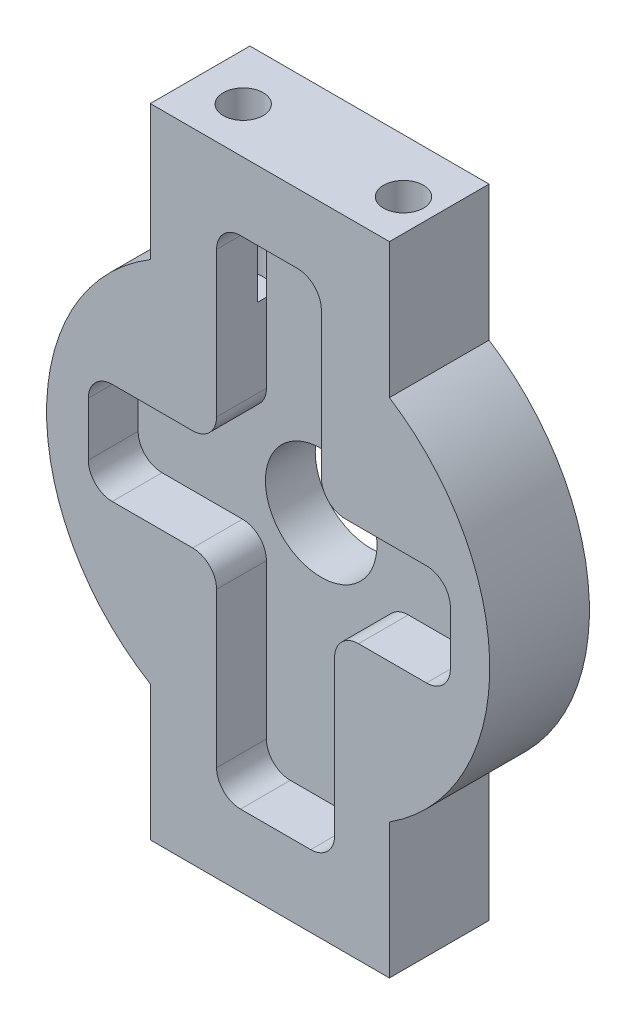
SolidWorks part; units mm, degrees
ref_plane "Front Plane" through (0, 0, 0) normal (0, 0, 1) x (1, 0, 0)
ref_plane "Top Plane" through (0, 0, 0) normal (0, 1, 0) x (1, 0, 0)
ref_plane "Right Plane" through (0, 0, 0) normal (1, 0, 0) x (0, 0, -1)
other "Graphic1"
ref_plane "Plane1" through (0, 0, 10) normal (0, 0, 1) x (1, 0, 0)
sketch "Sketch1" plane through (0, 0, 10) normal (0, 0, 1) x (1, 0, 0)
  line L0 (-246.9356, 240) -> (-246.9356, 200) construction
  line L1 (-257.9579, 223.6814) -> (-221.137, 223.6814) construction
  line L2 (-253, 240) -> (-241, 240)
  line L3 (-241, 240) -> (-241, 233.2195)
  line L4 (-241, 214.7805) -> (-241, 208)
  line L5 (-241, 208) -> (-253, 208)
  line L6 (-253, 208) -> (-253, 214.7805)
  line L7 (-253, 240) -> (-253, 233.2195)
  arc A0 (-241, 233.2195) -> (-241, 214.7805) centre (-246.9226, 224) cw
  arc A1 (-253, 233.2195) -> (-253, 214.7805) centre (-247.4317, 224) ccw
  circle A2 centre (-246.9226, 224) radius 2.8
  dimension "D1" = 12
extrude "Boss-Extrude1" add sketch "Sketch1" along normal blind 5
sketch "Sketch2" plane through (0, 0, 15) normal (0, 0, 1) x (1, 0, 0)
  line L0 (-249.6717, 236.5268) -> (-244.415, 236.5268)
  line L1 (-244.415, 236.5268) -> (-244.415, 226.8433)
  line L2 (-244.415, 226.8433) -> (-237.9409, 226.8433)
  line L3 (-237.9409, 226.8433) -> (-237.9409, 221.7526)
  line L4 (-237.9409, 221.7526) -> (-243.751, 221.7526)
  line L5 (-243.751, 221.7526) -> (-243.751, 211.6041)
  line L6 (-243.751, 211.6041) -> (-249.6717, 211.6041)
  line L7 (-249.6717, 211.6041) -> (-249.6717, 221.7526)
  line L8 (-249.6717, 221.7526) -> (-256.1089, 221.7526)
  line L9 (-256.1089, 221.7526) -> (-256.1089, 226.8433)
  line L10 (-256.1089, 226.8433) -> (-249.6717, 226.8433)
  line L11 (-249.6717, 226.8433) -> (-249.6717, 236.5268)
extrude "Cut-Extrude1" cut sketch "Sketch2" against normal blind 2.5
fillet "Fillet1" radius 1.2 12 edges at (-256.1089, 226.8433, 13.75) (-256.1089, 221.7526, 13.75) (-249.6717, 221.7526, 13.75) (-249.6717, 211.6041, 13.75) (-243.751, 211.6041, 13.75) (-243.751, 221.7526, 13.75) (-237.9409, 221.7526, 13.75) (-237.9409, 226.8433, 13.75) (-244.415, 226.8433, 13.75) (-249.6717, 226.8433, 13.75) (-249.6717, 236.5268, 13.75) (-244.415, 236.5268, 13.75)
sketch "Sketch3" plane through (0, 208, 0) normal (0, -1, 0) x (-1, 0, 0)
  line L0 (241, -15) -> (241, -10) construction
  line L1 (253, -10) -> (241, -10) construction
  circle A0 centre (250.9, -12.2) radius 1
  circle A1 centre (242.9, -12.2) radius 1
  dimension "D1" = 8
  dimension "D2" = 1.9
  dimension "D3" = 2.2
extrude "Cut-Extrude2" cut sketch "Sketch3" against normal blind 8
sketch "Sketch4" plane through (0, 240, 0) normal (0, 1, 0) x (1, 0, 0)
  circle A0 centre (-242.5988, -12.695) radius 1
  circle A1 centre (-250.6405, -12.695) radius 1
extrude "Cut-Extrude3" cut sketch "Sketch4" against normal blind 8
